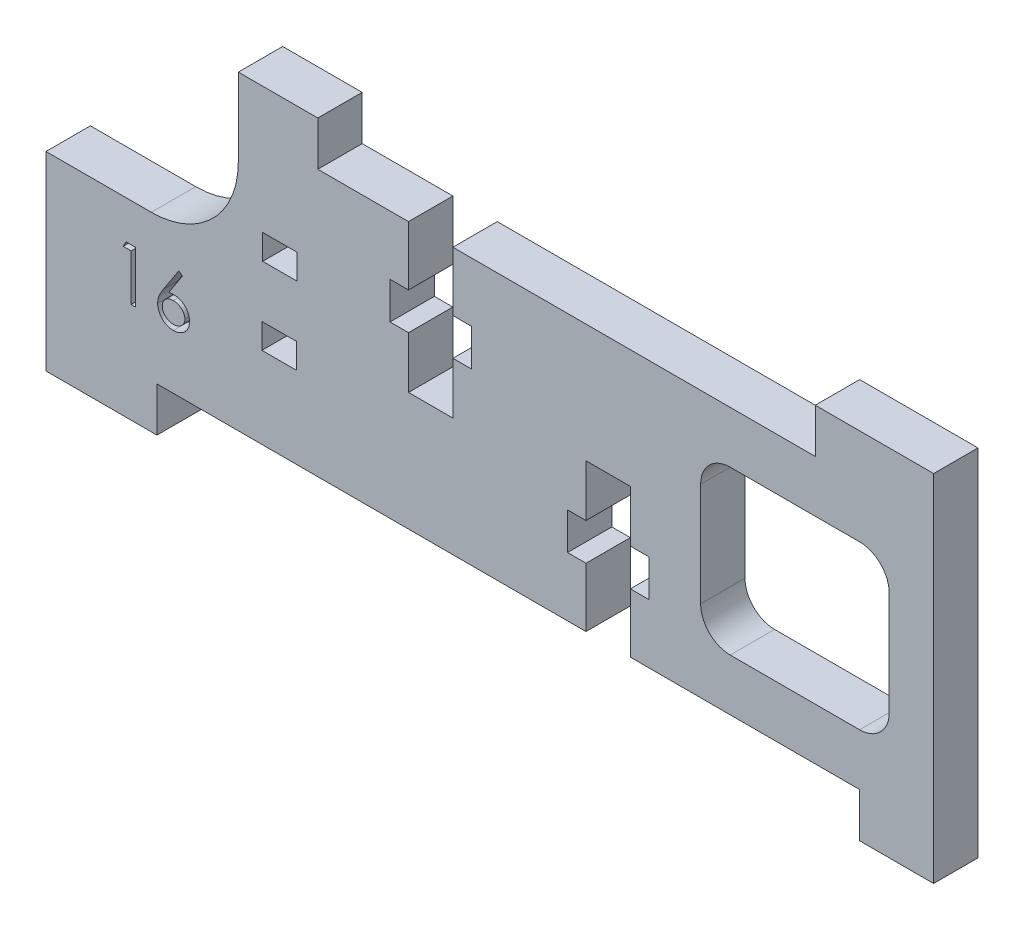
SolidWorks part; units mm, degrees
ref_plane "前视基准面" through (0, 0, 0) normal (0, 0, 1) x (1, 0, 0)
ref_plane "上视基准面" through (0, 0, 0) normal (0, 1, 0) x (1, 0, 0)
ref_plane "右视基准面" through (0, 0, 0) normal (1, 0, 0) x (0, 0, -1)
ref_plane "基准面4" through (0, 0, 3) normal (0, 0, 1) x (1, 0, 0)
sketch "草图1" plane through (0, 0, 3) normal (0, 0, 1) x (1, 0, 0)
  line L0 (23.2531, 5.5836) -> (24.503, 5.5836)
  line L1 (24.503, 5.5836) -> (24.503, 9.5836)
  line L2 (24.503, 9.5836) -> (18.3721, 9.5836)
  line L3 (18.3721, 9.5836) -> (18.3721, 12.5836)
  line L4 (18.3721, 12.5836) -> (12.9991, 12.5836)
  line L5 (12.9991, 12.5836) -> (12.9991, 7.3165)
  line L6 (7.1208, 1.4382) -> (0, 1.4382)
  line L7 (0, 1.4382) -> (0, -11.4164)
  line L8 (0, -11.4164) -> (7.4994, -11.4164)
  line L9 (7.4994, -11.4164) -> (7.4994, -8.4164)
  line L10 (7.4994, -8.4164) -> (36.5002, -8.4164)
  line L11 (36.5002, -8.4164) -> (36.5002, -4.4164)
  line L12 (36.5002, -4.4164) -> (35.2489, -4.4164)
  line L13 (35.2489, -4.4164) -> (35.2489, -1.9164)
  line L14 (35.2489, -1.9164) -> (36.5002, -1.9164)
  line L15 (36.5002, -1.9164) -> (36.5002, 1.5836)
  line L16 (36.5002, 1.5836) -> (39.5003, 1.5836)
  line L17 (39.5003, 1.5836) -> (39.5003, -1.9164)
  line L18 (39.5003, -1.9164) -> (40.7501, -1.9164)
  line L19 (40.7501, -1.9164) -> (40.7501, -4.4164)
  line L20 (40.7501, -4.4164) -> (39.5003, -4.4164)
  line L21 (39.5003, -4.4164) -> (39.5003, -8.4164)
  line L22 (39.5003, -8.4164) -> (54.9988, -8.4164)
  line L23 (54.9988, -8.4164) -> (54.9988, -11.4164)
  line L24 (54.9988, -11.4164) -> (59.9998, -11.4164)
  line L25 (59.9998, -11.4164) -> (59.9998, 12.5836)
  line L26 (59.9998, 12.5836) -> (51.9988, 12.5836)
  line L27 (51.9988, 12.5836) -> (51.9988, 9.5836)
  line L28 (51.9988, 9.5836) -> (27.5031, 9.5836)
  line L29 (27.5031, 9.5836) -> (27.5031, 5.5836)
  line L30 (27.5031, 5.5836) -> (28.7543, 5.5836)
  line L31 (28.7543, 5.5836) -> (28.7543, 3.0836)
  line L32 (28.7543, 3.0836) -> (27.5031, 3.0836)
  line L33 (27.5031, 3.0836) -> (27.5031, -0.4164)
  line L34 (27.5031, -0.4164) -> (24.503, -0.4164)
  line L35 (24.503, -0.4164) -> (24.503, 3.0836)
  line L36 (24.503, 3.0836) -> (23.2531, 3.0836)
  line L37 (23.2531, 3.0836) -> (23.2531, 5.5836)
  line L38 (46.2504, 6.0826) -> (54.9998, 6.0826)
  line L39 (56.9998, 4.0826) -> (56.9998, -2.9164)
  line L40 (54.9998, -4.9164) -> (46.2504, -4.9164)
  line L41 (44.2504, -2.9164) -> (44.2504, 4.0826)
  line L42 (14.6472, 4.0246) -> (16.9748, 4.0246)
  line L43 (16.9748, 4.0246) -> (16.9748, 2.3306)
  line L44 (16.9748, 2.3306) -> (14.6472, 2.3306)
  line L45 (14.6472, 2.3306) -> (14.6472, 4.0246)
  line L46 (14.5948, -1.2134) -> (16.9224, -1.2134)
  line L47 (16.9224, -1.2134) -> (16.9224, -2.9074)
  line L48 (16.9224, -2.9074) -> (14.5948, -2.9074)
  line L49 (14.5948, -2.9074) -> (14.5948, -1.2134)
  arc A0 (12.9991, 7.3165) -> (7.1208, 1.4382) centre (7.1208, 7.3165) cw
  arc A1 (54.9998, 6.0826) -> (56.9998, 4.0826) centre (54.9998, 4.0826) cw
  arc A2 (56.9998, -2.9164) -> (54.9998, -4.9164) centre (54.9998, -2.9164) cw
  arc A3 (46.2504, -4.9164) -> (44.2504, -2.9164) centre (46.2504, -2.9164) cw
  arc A4 (44.2504, 4.0826) -> (46.2504, 6.0826) centre (46.2504, 4.0826) cw
extrude "凸台-拉伸1" add sketch "草图1" against normal blind 3
sketch "草图2" plane through (0, 0, 3) normal (0, 0, 1) x (1, 0, 0)
  text T0 "16"
extrude "切除-拉伸1" cut sketch "草图2" against normal blind 1
